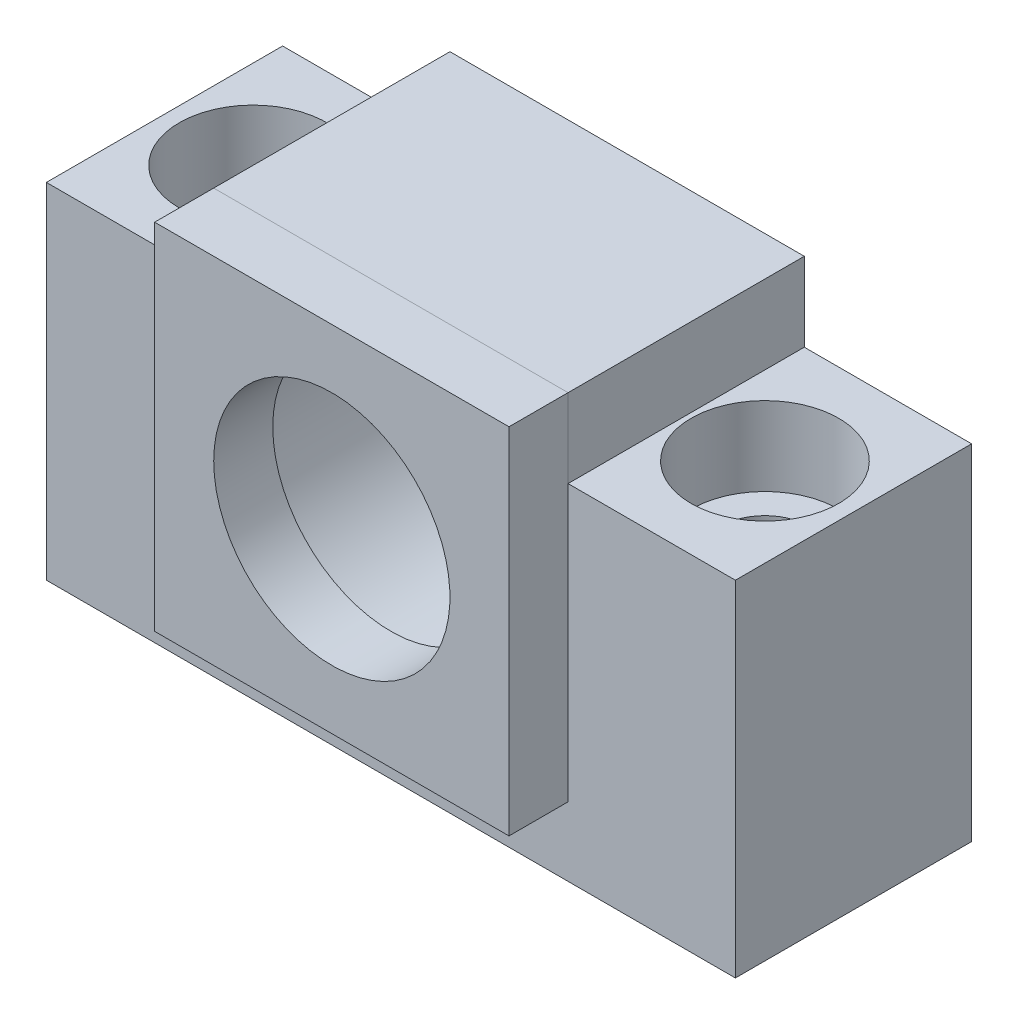
SolidWorks part; units mm, degrees
material "SKD11淬火HRC56-60"
ref_plane "前基準面" through (0, 0, 0) normal (0, 0, 1) x (1, 0, 0)
ref_plane "上基準面" through (0, 0, 0) normal (0, 1, 0) x (1, 0, 0)
ref_plane "右基準面" through (0, 0, 0) normal (1, 0, 0) x (0, 0, -1)
sketch "草图1" plane through (0, 0, 0) normal (0, 0, 1) x (1, 0, 0)
  line L1 (0, 0) -> (70, 0)
  line L2 (0, 0) -> (0, 43)
  line L3 (0, 43) -> (70, 43)
  line L4 (70, 0) -> (70, 43)
  dimension "D1" = 70
  dimension "D2" = 43
extrude "凸台-拉伸1" add sketch "草图1" along normal blind 24
sketch "草图2" plane through (0, 0, 24) normal (0, 0, 1) x (1, 0, 0)
  line L0 (35, 0) -> (35, 43) construction
  line L1 (0, 43) -> (17, 43)
  line L2 (0, 43) -> (0, 35)
  line L3 (0, 35) -> (17, 35)
  line L4 (17, 43) -> (17, 35)
  line L5 (0, 0) -> (70, 0) construction
  line L6 (70, 43) -> (0, 43) construction
  line L7 (53, 43) -> (53, 35)
  line L8 (70, 35) -> (53, 35)
  line L9 (70, 43) -> (70, 35)
  line L10 (70, 43) -> (53, 43)
  dimension "D1" = 36
  dimension "D2" = 35
extrude "切除-拉伸1" cut sketch "草图2" against normal through all
sketch "草图3" plane through (0, 0, 24) normal (0, 0, 1) x (1, 0, 0)
  line L0 (35, 0) -> (35, 43) construction
  line L1 (0, 0) -> (70, 0) construction
  line L2 (53, 43) -> (17, 43) construction
  circle A0 centre (35, 25) radius 15
  dimension "D1" = 30
  dimension "D2" = 25
extrude "切除-拉伸2" cut sketch "草图3" against normal blind 18
sketch "草图4" plane through (0, 0, 6) normal (0, 0, 1) x (1, 0, 0)
  circle A0 centre (35, 25) radius 12
  dimension "D1" = 24
extrude "切除-拉伸3" cut sketch "草图4" against normal through all
sketch "草图5" plane through (0, 0, 24) normal (0, 0, 1) x (1, 0, 0)
  line L0 (35, 25) -> (60.2212, 25) construction
  line L1 (17, 43) -> (53, 43)
  line L2 (17, 43) -> (17, 7)
  line L3 (17, 7) -> (53, 7)
  line L4 (53, 43) -> (53, 7)
  line L5 (35, 25) -> (35, 46.4992) construction
  dimension "D1" = 36
extrude "凸台-拉伸2" add sketch "草图5" along normal blind 6 separate body
sketch "草图6" plane through (0, 0, 24) normal (0, 0, -1) x (-1, 0, 0)
  circle A0 centre (-35, 25) radius 12 construction
  circle A1 centre (-35, 25) radius 12
extrude "切除-拉伸4" cut sketch "草图6" against normal through all
hole_wizard "M8 六角凹头螺钉的柱形沉头孔1" positions "草图8" profile "草图7" counterbore size "M8" standard "ISO" end condition through all
sketch "草图8" plane through (0, 35, 0) normal (0, 1, 0) x (-1, 0, 0)
  line L0 (0, 12) -> (-70, 12) construction
  line L1 (0, 0) -> (0, 24) construction
  line L2 (-70, 0) -> (-70, 24) construction
  line L3 (-35, 0) -> (-35, 24) construction
  line L4 (-53, 0) -> (-17, 0) construction
  line L5 (-53, 24) -> (-17, 24) construction
  point P0 (-61, 12)
  point P1 (-9, 12)
  dimension "D1" = 52
sketch "草图7" plane through (61, 35, 12) normal (1, 0, 0) x (0, 0, 1)
  line L0 (0, 0) -> (0, 35)
  line L1 (0, 35) -> (4.5, 35)
  line L3 (4.5, 35) -> (4.5, 8)
  line L4 (4.5, 8) -> (7.5, 8)
  line L5 (7.5, 8) -> (7.5, 0)
  line L7 (7.5, 0) -> (0, 0)
  line L11 (0, -6.35) -> (0, 107.95) construction
  dimension "通孔孔直径" = 9
  dimension "通孔孔深度" = 35
  dimension "柱形沉头孔直径" = 15
  dimension "柱形沉头孔深度" = 8
